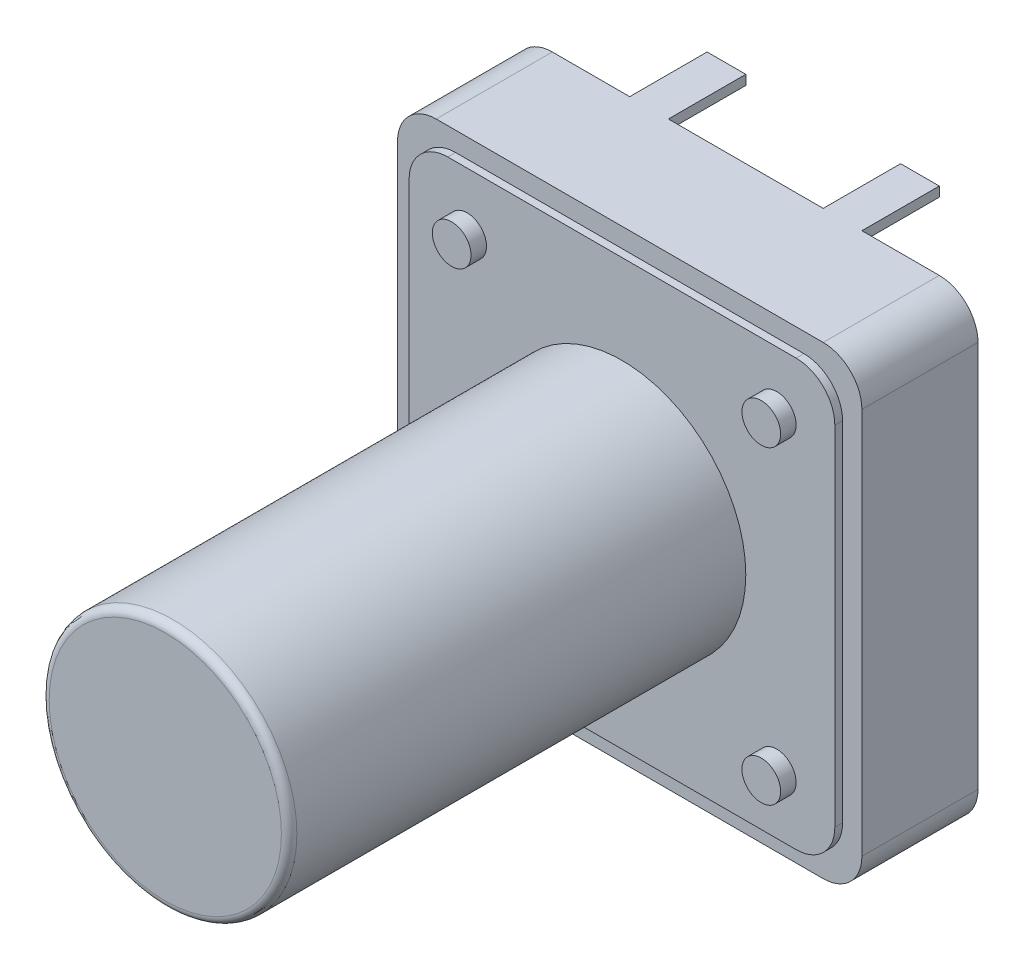
SolidWorks part; units mm, degrees
ref_plane "前视基准面" through (0, 0, 0) normal (0, 0, 1) x (1, 0, 0)
ref_plane "上视基准面" through (0, 0, 0) normal (0, 1, 0) x (1, 0, 0)
ref_plane "右视基准面" through (0, 0, 0) normal (1, 0, 0) x (0, 0, -1)
sketch "草图1" plane through (0, 0, 0) normal (0, 0, 1) x (1, 0, 0)
  line L1 (1, 0) -> (11, 0)
  line L2 (0, -1) -> (0, -11)
  line L3 (1, -12) -> (11, -12)
  line L4 (12, -1) -> (12, -11)
  arc A0 (1, -12) -> (0, -11) centre (1, -11) cw
  arc A1 (11, -12) -> (12, -11) centre (11, -11) ccw
  arc A2 (12, -1) -> (11, 0) centre (11, -1) ccw
  arc A3 (0, -1) -> (1, 0) centre (1, -1) cw
  point P13 (0, 0)
  dimension "D3" = 1
  dimension "D1" = 12
  dimension "D2" = 12
extrude "凸台-拉伸1" add sketch "草图1" along normal blind 3
sketch "草图2" plane through (0, 0, 3) normal (0, 0, 1) x (1, 0, 0)
  line L0 (6, 0) -> (6, -12) construction
  line L1 (11, 0) -> (1, 0) construction
  line L2 (1, -12) -> (11, -12) construction
  line L3 (0, -6) -> (12, -6) construction
  line L4 (0, -1) -> (0, -11) construction
  line L5 (12, -11) -> (12, -1) construction
  circle A0 centre (6, -6) radius 3.2
  dimension "D1" = 6.4
extrude "凸台-拉伸2" add sketch "草图2" along normal blind 12
fillet "圆角1" radius 0.2 1 edges at (9.2, -6, 15)
sketch "草图3" plane through (0, 0, 3) normal (0, 0, 1) x (1, 0, 0)
  line L0 (1.5, -0.5) -> (10.5, -0.5)
  line L1 (11.5, -1.5) -> (11.5, -10.5)
  line L2 (10.5, -11.5) -> (1.5, -11.5)
  line L3 (0.5, -10.5) -> (0.5, -1.5)
  circle A0 centre (6, -6) radius 5.5 construction
  arc A1 (0.5, -10.5) -> (1.5, -11.5) centre (1.5, -10.5) ccw
  arc A2 (10.5, -11.5) -> (11.5, -10.5) centre (10.5, -10.5) ccw
  arc A3 (11.5, -1.5) -> (10.5, -0.5) centre (10.5, -1.5) ccw
  arc A4 (1.5, -0.5) -> (0.5, -1.5) centre (1.5, -1.5) ccw
  dimension "D1" = 11
  dimension "D2" = 1
extrude "凸台-拉伸3" add sketch "草图3" along normal blind 0.2
sketch "草图4" plane through (0, 0, 3.2) normal (0, 0, 1) x (1, 0, 0)
  line L0 (11, 0) -> (1, 0) construction
  line L1 (0, -1) -> (0, -11) construction
  line L2 (6, -0.5) -> (6, -11.5) construction
  line L3 (10.5, -0.5) -> (1.5, -0.5) construction
  line L4 (1.5, -11.5) -> (10.5, -11.5) construction
  line L5 (0.5, -6) -> (11.5, -6) construction
  line L6 (0.5, -1.5) -> (0.5, -10.5) construction
  line L7 (11.5, -10.5) -> (11.5, -1.5) construction
  circle A0 centre (2, -2) radius 0.5
  circle A1 centre (10, -2) radius 0.5
  circle A2 centre (10, -10) radius 0.5
  circle A3 centre (2, -10) radius 0.5
  dimension "D1" = 1
  dimension "D2" = 2
  dimension "D3" = 2
extrude "凸台-拉伸4" add sketch "草图4" along normal blind 0.4
sketch "草图5" plane through (0, 0, 0) normal (0, 0, -1) x (-1, 0, 0)
  line L0 (-6, -12) -> (-6, 0) construction
  line L1 (-1, -12) -> (-11, -12) construction
  line L2 (-11, 0) -> (-1, 0) construction
  line L3 (-3.5, -12.7527) -> (-3.5, -10.7949) construction
  line L4 (-3, -12) -> (-3, -11.75)
  line L5 (-4, -12) -> (-4, -11.75)
  line L6 (-3, -12) -> (-4, -12)
  line L7 (-3, -11.75) -> (-4, -11.75)
  line L8 (-8, -12) -> (-8, -11.75)
  line L9 (-9, -11.75) -> (-8, -11.75)
  line L10 (-9, -12) -> (-8, -12)
  line L11 (-9, -12) -> (-9, -11.75)
  line L12 (0, -6) -> (-12, -6) construction
  line L13 (0, -1) -> (0, -11) construction
  line L14 (-12, -11) -> (-12, -1) construction
  line L15 (-9, 0) -> (-8, 0)
  line L16 (-9, 0) -> (-9, -0.25)
  line L17 (-9, -0.25) -> (-8, -0.25)
  line L18 (-8, 0) -> (-8, -0.25)
  line L19 (-4, 0) -> (-4, -0.25)
  line L20 (-3, 0) -> (-3, -0.25)
  line L21 (-3, 0) -> (-4, 0)
  line L22 (-3, -0.25) -> (-4, -0.25)
  dimension "D1" = 2.5
  dimension "D2" = 0.25
  dimension "D3" = 1
extrude "凸台-拉伸5" add sketch "草图5" along normal blind 2
